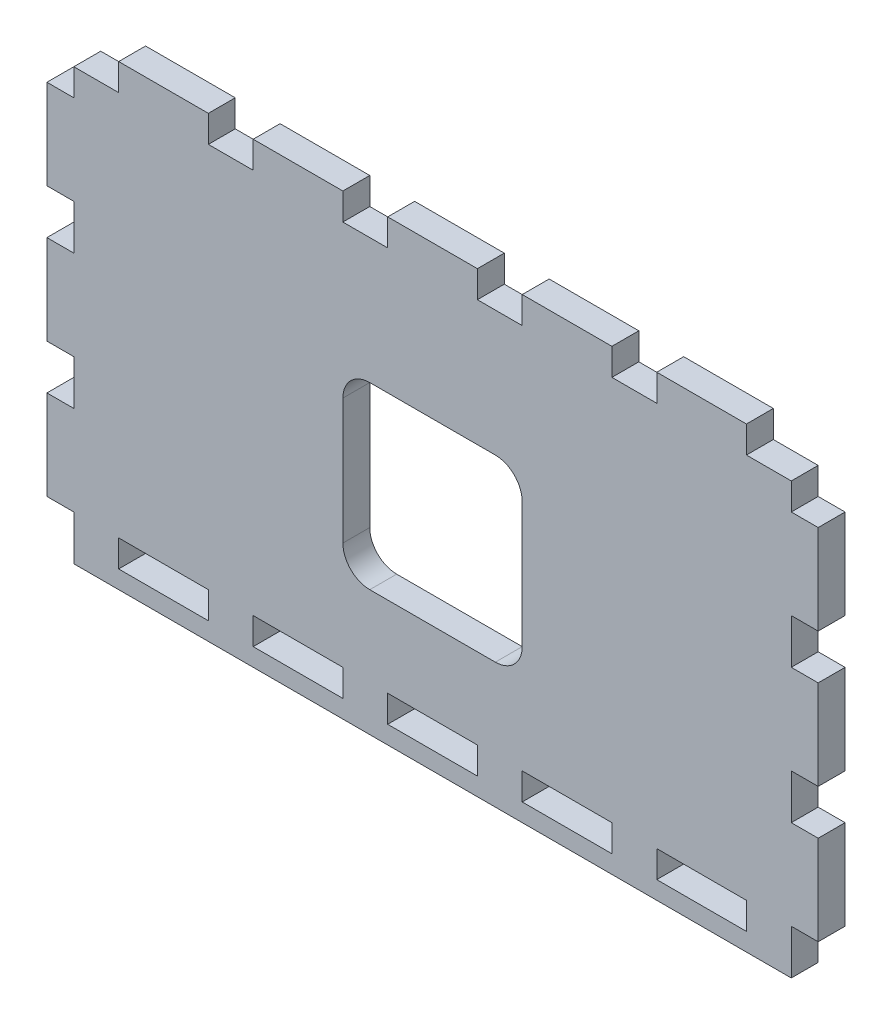
SolidWorks part; units mm, degrees
material "轻木"
ref_plane "前视基准面" through (0, 0, 0) normal (0, 0, 1) x (1, 0, 0)
ref_plane "上视基准面" through (0, 0, 0) normal (0, 1, 0) x (1, 0, 0)
ref_plane "右视基准面" through (0, 0, 0) normal (1, 0, 0) x (0, 0, -1)
sketch "草图1" plane through (0, 0, 0) normal (0, 0, 1) x (1, 0, 0)
  line L1 (-40, 24) -> (-35, 24)
  line L2 (-40, 24) -> (-40, 21)
  line L3 (-40, -24) -> (40, -24)
  line L4 (40, 24) -> (40, 21)
  line L5 (-40, 24) -> (40, -24) construction
  line L6 (-40, -24) -> (40, 24) construction
  line L7 (-40, 21) -> (-43, 21)
  line L9 (-40, 11) -> (-43, 11)
  line L10 (-43, 21) -> (-43, 11)
  line L11 (-40, 6) -> (-43, 6)
  line L12 (-43, 6) -> (-43, -4)
  line L13 (-40, -4) -> (-43, -4)
  line L15 (-40, -9) -> (-43, -9)
  line L16 (-43, -9) -> (-43, -19)
  line L17 (-40, -19) -> (-43, -19)
  line L18 (0, -55) -> (0, 55) construction
  line L19 (40, -9) -> (43, -9)
  line L20 (43, -9) -> (43, -19)
  line L21 (40, -19) -> (43, -19)
  line L23 (40, 6) -> (43, 6)
  line L24 (43, 6) -> (43, -4)
  line L25 (40, -4) -> (43, -4)
  line L27 (40, 11) -> (43, 11)
  line L28 (43, 21) -> (43, 11)
  line L29 (40, 21) -> (43, 21)
  line L31 (-10, -22) -> (-10, -19)
  line L32 (-25, -22) -> (-35, -22)
  line L33 (-25, -22) -> (-25, -19)
  line L34 (-25, -19) -> (-35, -19)
  line L35 (-35, -22) -> (-35, -19)
  line L36 (-10, -22) -> (-20, -22)
  line L37 (-20, -22) -> (-20, -19)
  line L38 (-10, -19) -> (-20, -19)
  line L39 (5, -22) -> (5, -19)
  line L40 (5, -22) -> (-5, -22)
  line L41 (-5, -22) -> (-5, -19)
  line L42 (5, -19) -> (-5, -19)
  line L43 (20, -22) -> (20, -19)
  line L44 (20, -22) -> (10, -22)
  line L45 (10, -22) -> (10, -19)
  line L46 (20, -19) -> (10, -19)
  line L47 (35, -22) -> (35, -19)
  line L48 (35, -22) -> (25, -22)
  line L49 (25, -22) -> (25, -19)
  line L50 (35, -19) -> (25, -19)
  line L51 (-20, 24) -> (-20, 27)
  line L53 (-35, 24) -> (-35, 27)
  line L54 (-35, 27) -> (-25, 27)
  line L55 (-25, 24) -> (-25, 27)
  line L57 (-10, 24) -> (-10, 27)
  line L58 (-20, 27) -> (-10, 27)
  line L59 (-5, 24) -> (-5, 27)
  line L61 (5, 24) -> (5, 27)
  line L62 (-5, 27) -> (5, 27)
  line L63 (10, 24) -> (10, 27)
  line L65 (20, 24) -> (20, 27)
  line L66 (10, 27) -> (20, 27)
  line L67 (25, 24) -> (25, 27)
  line L69 (35, 24) -> (35, 27)
  line L70 (25, 27) -> (35, 27)
  line L71 (-25, 24) -> (-20, 24)
  line L72 (-10, 24) -> (-5, 24)
  line L73 (5, 24) -> (10, 24)
  line L74 (20, 24) -> (25, 24)
  line L75 (35, 24) -> (40, 24)
  line L76 (40, 11) -> (40, 6)
  line L77 (40, -4) -> (40, -9)
  line L78 (40, -19) -> (40, -24)
  line L80 (-40, -19) -> (-40, -24)
  line L81 (-40, -4) -> (-40, -9)
  line L83 (-40, 11) -> (-40, 6)
  point P0 (0, 0)
  dimension "D1" = 80
  dimension "D2" = 48
  dimension "D3" = 3
  dimension "D4" = 10
  dimension "D5" = 3
  dimension "D7" = 10
  dimension "D8" = 3
  dimension "D9" = 2
  dimension "D10" = 5
  dimension "D12" = 5
  dimension "D6" = 3
  dimension "D11" = 5
extrude "凸台-拉伸1" add sketch "草图1" along normal blind 3
sketch "草图2" plane through (0, 0, 3) normal (0, 0, 1) x (1, 0, 0)
  line L1 (-10, 10) -> (10, 10)
  line L2 (-10, 10) -> (-10, -10)
  line L3 (-10, -10) -> (10, -10)
  line L4 (10, 10) -> (10, -10)
  line L5 (-10, 10) -> (10, -10) construction
  line L6 (-10, -10) -> (10, 10) construction
  point P0 (0, 0)
  dimension "D1" = 20
  dimension "D2" = 20
extrude "切除-拉伸1" cut sketch "草图2" against normal blind 10
fillet "圆角1" radius 3 4 edges at (-10, 10, 1.5) (10, 10, 1.5) (10, -10, 1.5) (-10, -10, 1.5)
